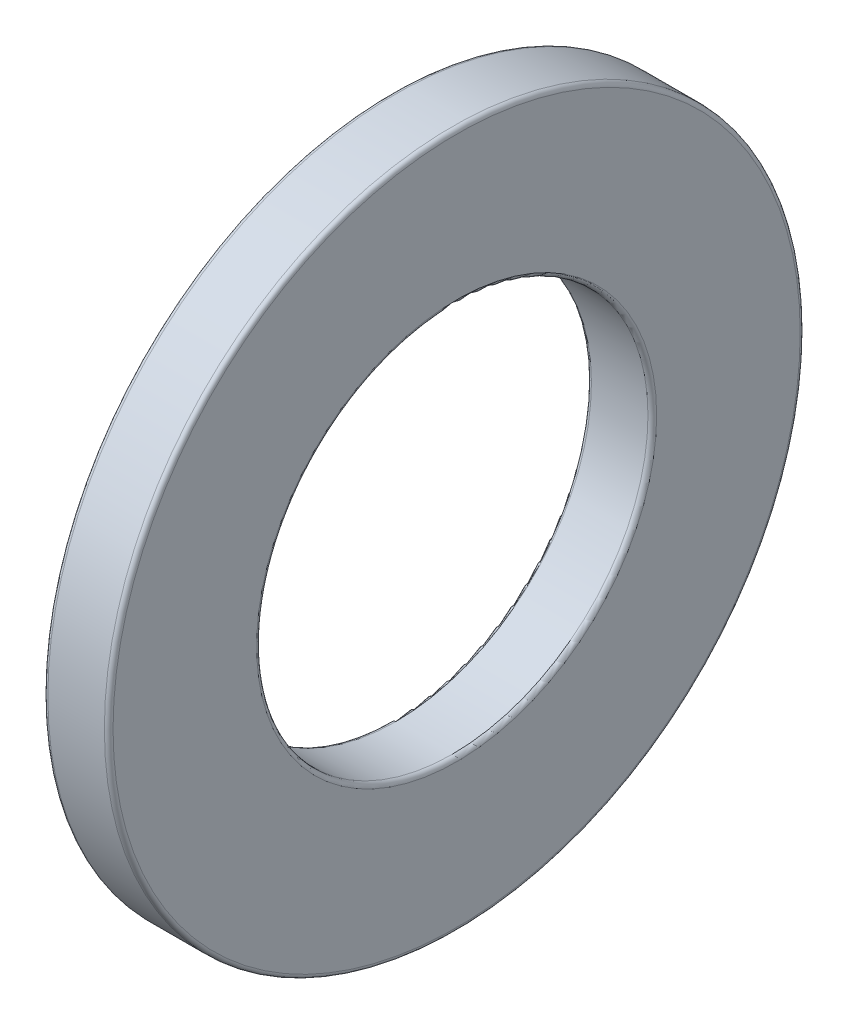
SolidWorks part; units mm, degrees
ref_plane "Front Plane" through (0, 0, 0) normal (0, 0, 1) x (1, 0, 0)
ref_plane "Top Plane" through (0, 0, 0) normal (0, 1, 0) x (1, 0, 0)
ref_plane "Right Plane" through (0, 0, 0) normal (1, 0, 0) x (0, 0, -1)
sketch "Sketch1" plane through (0, 0, 0) normal (1, 0, 0) x (0, 0, -1)
  circle A0 centre (0, 0) radius 4
  circle A1 centre (0, 0) radius 2.25
  dimension "D1" = 4.5
  dimension "D2" = 8
extrude "Boss-Extrude1" add sketch "Sketch1" along normal blind 0.75
fillet "Fillet1" radius 0.05 4 edges at (0, 0, -4) (0, 0, -2.25) (0.75, 0, -2.25) (0.75, 0, -4)
